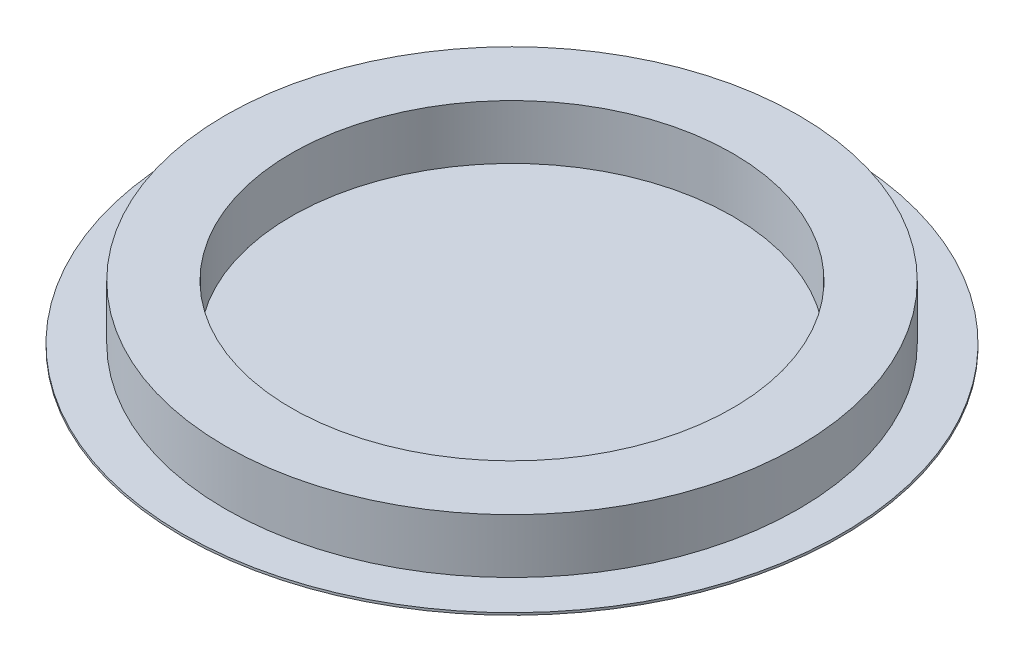
SolidWorks part; units mm, degrees
ref_plane "Front Plane" through (0, 0, 0) normal (0, 0, 1) x (1, 0, 0)
ref_plane "Top Plane" through (0, 0, 0) normal (0, 1, 0) x (1, 0, 0)
ref_plane "Right Plane" through (0, 0, 0) normal (1, 0, 0) x (0, 0, -1)
sketch "Sketch1" plane through (0, 0, 0) normal (0, 1, 0) x (1, 0, 0)
  circle A0 centre (0, 0) radius 11.5
  dimension "D1" = 23
extrude "Boss-Extrude1" add sketch "Sketch1" along normal blind 0.08
sketch "Sketch2" plane through (0, 0.08, 0) normal (0, 1, 0) x (1, 0, 0)
  circle A0 centre (0, 0) radius 10
  circle A1 centre (0, 0) radius 7.7
  dimension "D1" = 15.4
  dimension "D2" = 20
extrude "Boss-Extrude2" add sketch "Sketch2" along normal blind 1.9
